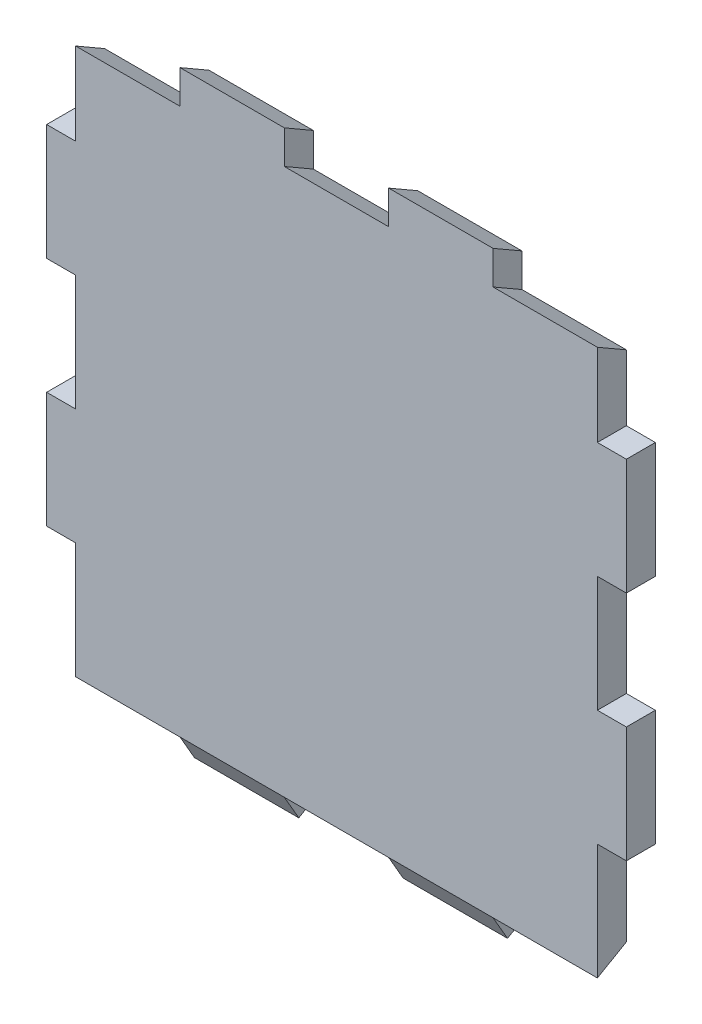
SolidWorks part; units mm, degrees
ref_plane "Front Plane" through (0, 0, 0) normal (0, 0, 1) x (1, 0, 0)
ref_plane "Top Plane" through (0, 0, 0) normal (0, 1, 0) x (1, 0, 0)
ref_plane "Right Plane" through (0, 0, 0) normal (1, 0, 0) x (0, 0, -1)
sketch "Esquisse1" plane through (0, 0, 0) normal (0, 0, 1) x (1, 0, 0)
  line L1 (0, 0) -> (-90, 0)
  line L2 (0, 0) -> (0, -100)
  line L3 (0, -100) -> (-90, -100)
  line L4 (-90, 0) -> (-90, -100)
  line L5 (-45, -100) -> (-45, 0) construction
  line L6 (0, -50) -> (-90, -50) construction
  point P84 (-45, -50)
  dimension "D1" = 100
  dimension "D2" = 90
extrude "Boss.-Extru.1" add sketch "Esquisse1" along normal blind 5
sketch "Esquisse2" plane through (0, 0, 0) normal (1, 0, 0) x (0, 0, -1)
  line L0 (0, -11.547) -> (-5, -8.6603)
  line L1 (76.6025, -55.7735) -> (61.782, -47.2169) construction
  line L4 (0, -100) -> (0, 0)
  line L5 (0, 0) -> (-5, 0)
  line L6 (-5, 0) -> (-5, -100)
  line L7 (-5, -100) -> (0, -100)
  line L8 (0, -11.547) -> (0, 0)
  line L9 (0, 0) -> (-5, 0)
  line L10 (-5, 0) -> (-5, -8.6603)
  dimension "D1" = 0
extrude "Enlèv. mat.-Extru.1" cut sketch "Esquisse2" against normal through all
sketch "Esquisse3" plane through (0, 0, 0) normal (1, 0, 0) x (0, 0, -1)
  line L0 (-5, -100) -> (-5, -102.8868)
  line L1 (-5, -102.8868) -> (0, -100)
  line L2 (0, -100) -> (-5, -100)
extrude "Boss.-Extru.2" add sketch "Esquisse3" against normal through all
sketch "Esquisse6" plane through (0, 0, 5) normal (0, 0, 1) x (1, 0, 0)
  line L1 (-72, -99.3868) -> (-54, -99.3868)
  line L2 (-72, -99.3868) -> (-72, -105.3868)
  line L3 (-72, -105.3868) -> (-54, -105.3868)
  line L4 (-54, -99.3868) -> (-54, -105.3868)
  line L5 (-63, -105.3868) -> (-63, -99.3868) construction
  line L6 (-72, -102.3868) -> (-54, -102.3868) construction
  line L7 (-90, -8.6603) -> (-90, -102.8868) construction
  line L8 (-36, -99.3868) -> (-18, -99.3868)
  line L9 (-36, -99.3868) -> (-36, -105.3868)
  line L10 (-36, -105.3868) -> (-18, -105.3868)
  line L11 (-18, -99.3868) -> (-18, -105.3868)
  line L12 (-27, -105.3868) -> (-27, -99.3868) construction
  line L13 (-36, -102.3868) -> (-18, -102.3868) construction
  line L16 (-90, -102.8868) -> (0, -102.8868) construction
  point P14 (-72, -109.2037)
  point P15 (0, 0)
  point P112 (-27, -102.3868)
  point P192 (-63, -102.3868)
  dimension "D1" = 18
  dimension "D2" = 18
  dimension "D3" = 18
  dimension "D4" = 18
  dimension "D6" = 2.5
  dimension "D7" = 3.5
extrude "Boss.-Extru.3" [suppressed] add sketch "Esquisse6" against normal blind 5
sketch "Esquisse7" [suppressed] plane through (-72, 0, 0) normal (-1, 0, 0) x (0, 0, 1)
  line L0 (5, -102.8868) -> (5, -105.3868)
  line L1 (5, -105.3868) -> (3.5566, -105.3868)
  line L2 (0, -105.3868) -> (5, -105.3868) construction
  line L3 (2.5, -107.2169) -> (5, -102.8868) construction
  line L4 (3.5566, -105.3868) -> (5, -102.8868)
extrude "Enlèv. mat.-Extru.2" [suppressed] cut sketch "Esquisse7" against normal through all
sketch "Esquisse10" plane through (0, 0, 0) normal (0, 0, -1) x (-1, 0, 0)
  line L0 (90, -11.547) -> (0, -11.547) construction
  line L1 (18, 3.453) -> (36, 3.453)
  line L2 (18, 3.453) -> (18, -11.547)
  line L3 (18, -11.547) -> (36, -11.547)
  line L4 (36, 3.453) -> (36, -11.547)
  line L5 (27, -11.547) -> (27, 3.453) construction
  line L6 (18, -4.047) -> (36, -4.047) construction
  line L8 (54, 3.453) -> (72, 3.453)
  line L9 (54, 3.453) -> (54, -11.547)
  line L10 (54, -11.547) -> (72, -11.547)
  line L11 (72, 3.453) -> (72, -11.547)
  line L12 (63, -11.547) -> (63, 3.453) construction
  line L13 (54, -4.047) -> (72, -4.047) construction
  point P84 (63, -4.047)
  point P136 (27, -4.047)
  dimension "D1" = 18
  dimension "D2" = 18
  dimension "D3" = 18
  dimension "D4" = 18
  dimension "D5" = 15
extrude "Boss.-Extru.4" add sketch "Esquisse10" against normal through all
sketch "Esquisse11" plane through (-18, 0, 0) normal (1, 0, 0) x (0, 0, -1)
  line L0 (0, -5.7735) -> (-5, -2.8868)
  line L1 (-5, -2.8868) -> (12.3205, -12.8868) construction
  line L4 (-5, -8.6603) -> (0, -11.547)
  line L5 (0, -11.547) -> (0, 3.453)
  line L6 (0, 3.453) -> (-5, 3.453)
  line L7 (-5, 3.453) -> (-5, -8.6603)
  line L9 (0, -5.7735) -> (0, 3.453)
  line L10 (0, 3.453) -> (-5, 3.453)
  line L11 (-5, 3.453) -> (-5, -2.8868)
  dimension "D1" = 0
extrude "Enlèv. mat.-Extru.3" cut sketch "Esquisse11" against normal through all
sketch "Esquisse12" plane through (0, 0, 0) normal (0, 0, -1) x (-1, 0, 0)
  line L0 (90, -100) -> (0, -100) construction
  line L1 (18, -100) -> (36, -100)
  line L2 (18, -100) -> (18, -112)
  line L3 (18, -112) -> (36, -112)
  line L4 (36, -100) -> (36, -112)
  line L5 (27, -112) -> (27, -100) construction
  line L6 (18, -106) -> (36, -106) construction
  line L7 (0, -102.8868) -> (0, -100) construction
  line L8 (54, -100) -> (72, -100)
  line L9 (54, -100) -> (54, -112)
  line L10 (54, -112) -> (72, -112)
  line L11 (72, -100) -> (72, -112)
  line L12 (63, -112) -> (63, -100) construction
  line L13 (54, -106) -> (72, -106) construction
  point P64 (63, -106)
  point P136 (27, -106)
  dimension "D1" = 18
  dimension "D2" = 18
  dimension "D3" = 18
  dimension "D4" = 18
  dimension "D5" = 12
extrude "Boss.-Extru.5" add sketch "Esquisse12" against normal blind 5
sketch "Esquisse13" plane through (-18, 0, 0) normal (1, 0, 0) x (0, 0, -1)
  line L0 (-5, -102.8868) -> (-2.5, -107.2169)
  line L1 (-2.5, -107.2169) -> (0, -105.7735)
  line L2 (84.1025, -57.2169) -> (66.782, -67.2169) construction
  line L3 (-5, -102.8868) -> (-2.5, -107.2169)
  line L4 (0, -112) -> (0, -100)
  line L5 (0, -100) -> (-5, -102.8868)
  line L6 (-5, -102.8868) -> (-5, -112)
  line L7 (-5, -112) -> (0, -112)
  line L8 (0, -112) -> (0, -105.7735)
  line L10 (-5, -102.8868) -> (-5, -112)
  line L11 (-5, -112) -> (0, -112)
  line M6 (0, -112) -> (0, -100)
  line M8 (-5, -102.8868) -> (-5, -112)
  line M9 (-5, -112) -> (0, -112)
  dimension "D1" = 0
extrude "Enlèv. mat.-Extru.4" cut sketch "Esquisse13" against normal through all contours L1 L0 M8 M9 M6
sketch "Esquisse14" plane through (0, 0, 5) normal (0, 0, 1) x (1, 0, 0)
  line L0 (0, -102.8868) -> (0, -8.6603) construction
  line L1 (0, -22.8868) -> (5, -22.8868)
  line L2 (0, -22.8868) -> (0, -42.8868)
  line L3 (0, -42.8868) -> (5, -42.8868)
  line L4 (5, -22.8868) -> (5, -42.8868)
  line L5 (2.5, -42.8868) -> (2.5, -22.8868) construction
  line L6 (0, -32.8868) -> (5, -32.8868) construction
  line L7 (5, -102.8868) -> (5, -82.8868) construction
  line L8 (0, -2.8868) -> (5, -2.8868) construction
  line L9 (0, -62.8868) -> (5, -62.8868)
  line L10 (0, -62.8868) -> (0, -82.8868)
  line L11 (0, -82.8868) -> (5, -82.8868)
  line L12 (5, -62.8868) -> (5, -82.8868)
  line L13 (2.5, -82.8868) -> (2.5, -62.8868) construction
  line L14 (0, -72.8868) -> (5, -72.8868) construction
  line L15 (-45, -2.8868) -> (-45, -107.2169) construction
  line L16 (-54, -2.8868) -> (-36, -2.8868) construction
  line L18 (-90, -72.8868) -> (-95, -72.8868) construction
  line L19 (-92.5, -82.8868) -> (-92.5, -62.8868) construction
  line L20 (-90, -32.8868) -> (-95, -32.8868) construction
  line L21 (-92.5, -42.8868) -> (-92.5, -22.8868) construction
  line L22 (-95, -62.8868) -> (-95, -82.8868)
  line L23 (-90, -82.8868) -> (-95, -82.8868)
  line L24 (-90, -62.8868) -> (-90, -82.8868)
  line L25 (-90, -62.8868) -> (-95, -62.8868)
  line L26 (-95, -22.8868) -> (-95, -42.8868)
  line L27 (-90, -42.8868) -> (-95, -42.8868)
  line L28 (-90, -22.8868) -> (-90, -42.8868)
  line L29 (-90, -22.8868) -> (-95, -22.8868)
  line L30 (-36, -107.2169) -> (-54, -107.2169) construction
  point P22 (-45, -107.2169)
  point P40 (-92.5, -32.8868)
  point P41 (-92.5, -72.8868)
  point P98 (2.5, -72.8868)
  point P128 (2.5, -32.8868)
  dimension "D1" = 20
  dimension "D2" = 20
  dimension "D3" = 20
  dimension "D4" = 20
extrude "Boss.-Extru.6" add sketch "Esquisse14" against normal through all
